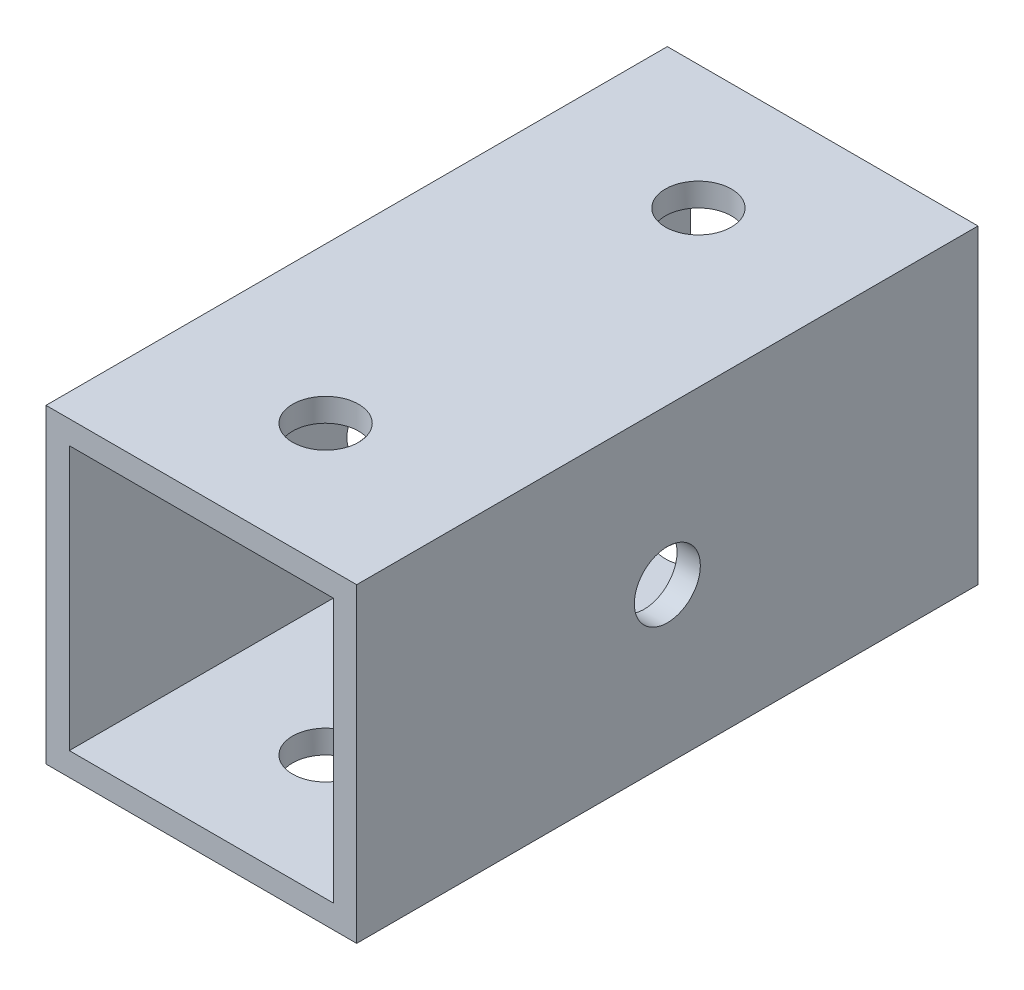
SolidWorks part; units mm, degrees
ref_plane "Front Plane" through (0, 0, 0) normal (0, 0, 1) x (1, 0, 0)
ref_plane "Top Plane" through (0, 0, 0) normal (0, 1, 0) x (1, 0, 0)
ref_plane "Right Plane" through (0, 0, 0) normal (1, 0, 0) x (0, 0, -1)
sketch "Sketch1" plane through (0, 0, 0) normal (0, 0, 1) x (1, 0, 0)
  line L0 (-8.5, -8.5) -> (8.5, -8.5)
  line L1 (-10, -10) -> (10, -10)
  line L2 (-10, -10) -> (-10, 10)
  line L3 (-10, 10) -> (10, 10)
  line L4 (10, -10) -> (10, 10)
  line L5 (-10, -10) -> (10, 10) construction
  line L6 (-10, 10) -> (10, -10) construction
  line L7 (8.5, -8.5) -> (8.5, 8.5)
  line L8 (-8.5, 8.5) -> (8.5, 8.5)
  line L9 (-8.5, -8.5) -> (-8.5, 8.5)
  point P0 (0, 0)
  dimension "D1" = 20
  dimension "D3" = 20
  dimension "D2" = 1.5
extrude "Boss-Extrude1" add sketch "Sketch1" against normal blind 40
sketch "Sketch2" plane through (0, 10, 0) normal (0, 1, 0) x (1, 0, 0)
  line L0 (10, 0) -> (-10, 0) construction
  line L1 (-10, 20) -> (10, 20) construction
  line L2 (-10, 40) -> (-10, 0) construction
  line L3 (10, 40) -> (10, 0) construction
  circle A0 centre (0, 8) radius 2.125
  circle A1 centre (0, 32) radius 2.125
  dimension "D1" = 4.25
  dimension "D2" = 8
extrude "Cut-Extrude1" cut sketch "Sketch2" against normal through all
sketch "Sketch3" plane through (10, 0, 0) normal (1, 0, 0) x (0, 0, -1)
  line L0 (20, 10) -> (20, -10) construction
  line L1 (40, 10) -> (0, 10) construction
  line L2 (40, -10) -> (0, -10) construction
  circle A0 centre (20, 0) radius 2.125
  dimension "D1" = 4.25
extrude "Cut-Extrude2" cut sketch "Sketch3" against normal through all
